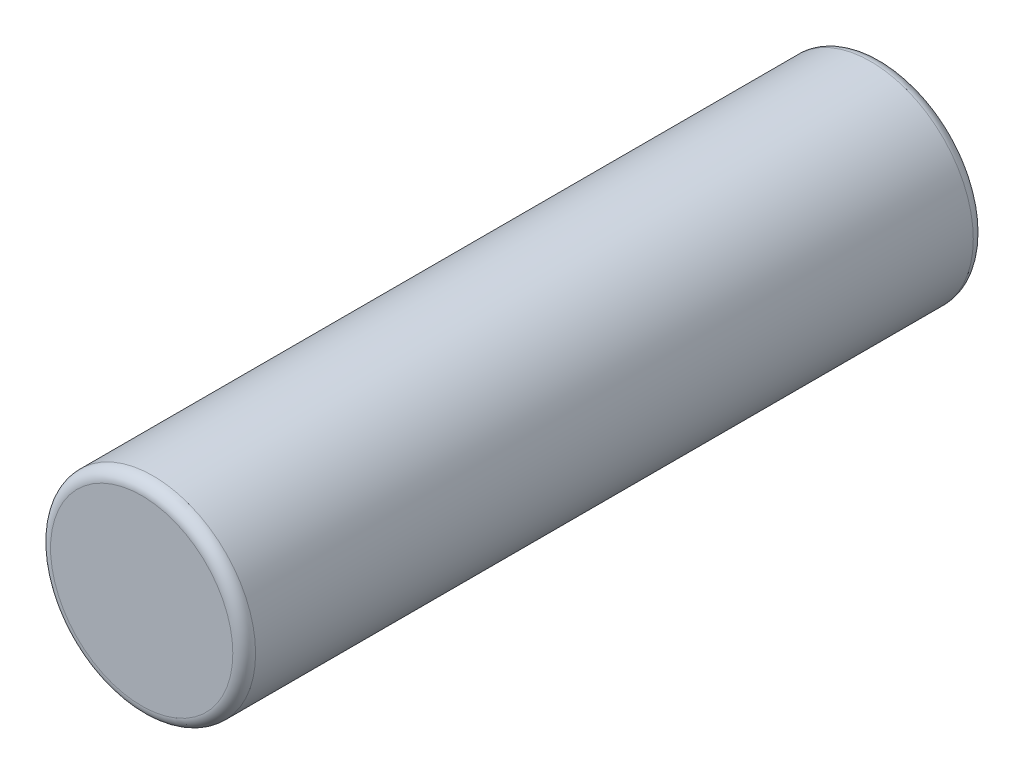
SolidWorks part; units mm, degrees
material "AISI 1020"
ref_plane "Face" through (0, 0, 0) normal (0, 0, 1) x (1, 0, 0)
ref_plane "Dessus" through (0, 0, 0) normal (0, 1, 0) x (1, 0, 0)
ref_plane "Droite" through (0, 0, 0) normal (1, 0, 0) x (0, 0, -1)
sketch "Esquisse1" plane through (0, 0, 0) normal (0, 0, 1) x (1, 0, 0)
  circle A0 centre (0, 0) radius 9
  dimension "D1" = 18
extrude "Boss.-Extru.1" add sketch "Esquisse1" along normal mid plane 65
fillet "Congé1" radius 1 2 edges at (9, 0, 32.5) (9, 0, -32.5)
